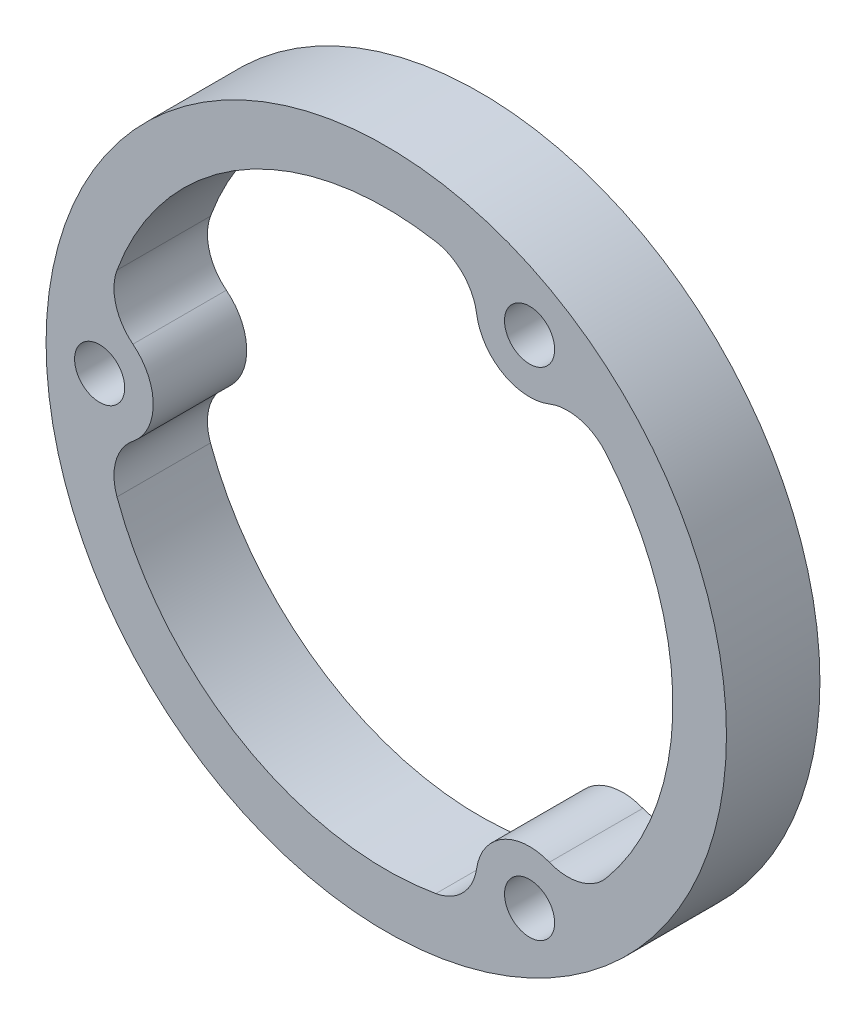
SolidWorks part; units mm, degrees
material "6061-T6 (SS)"
ref_plane "Front Plane" through (0, 0, 0) normal (0, 0, 1) x (1, 0, 0)
ref_plane "Top Plane" through (0, 0, 0) normal (0, 1, 0) x (1, 0, 0)
ref_plane "Right Plane" through (0, 0, 0) normal (1, 0, 0) x (0, 0, -1)
sketch "Sketch1" plane through (0, 0, 0) normal (0, 0, 1) x (1, 0, 0)
  arc A0 (19.0584, -22.136) -> (19.0584, 22.136) centre (0, 0) ccw
  circle A1 centre (0, 0) radius 34.671
  arc A4 (-28.6995, -5.4371) -> (-28.6995, 5.4371) centre (-29.21, 0) ccw
  arc A5 (9.6411, 27.5731) -> (19.0584, 22.136) centre (14.605, 25.2966) ccw
  arc A6 (19.0584, -22.136) -> (9.6411, -27.5731) centre (14.605, -25.2966) ccw
  arc A7 (9.6411, 27.5731) -> (-28.6995, 5.4371) centre (0, 0) ccw
  arc A8 (-28.6995, -5.4371) -> (9.6411, -27.5731) centre (0, 0) ccw
  point P14 (0, 0)
  dimension "D1" = 58.42
  dimension "D2" = 69.342
  dimension "D4" = 3
  dimension "D3" = 30
  dimension "D5" = 120
  dimension "D6" = 120
extrude "Boss-Extrude1" add sketch "Sketch1" along normal blind 9.525
fillet "Fillet1" radius 5.08 6 edges at (9.6411, 27.5731, 4.7625) (19.0584, 22.136, 4.7625) (9.6411, -27.5731, 4.7625) (19.0584, -22.136, 4.7625) (-28.6995, 5.4371, 4.7625) (-28.6995, -5.4371, 4.7625)
sketch "Sketch2" plane through (0, 0, 0) normal (0, 0, -1) x (-1, 0, 0)
  circle A0 centre (-14.605, 25.2966) radius 4.0005
  arc A1 (-16.6198, 20.2209) -> (-9.2019, 24.5036) centre (-14.605, 25.2966) ccw construction
  circle A2 centre (29.21, 0) radius 4.0005
  circle A3 centre (-14.605, -25.2966) radius 4.0005
  point P11 (0, 0)
  dimension "D1" = 8.001
  dimension "D2" = 3
extrude "Cut-Extrude1" cut sketch "Sketch2" against normal blind 5.08
hole_wizard "#10 Clearance Hole1" positions "Sketch3" profile "Sketch4" hole size "#10" standard "ANSI Inch" end condition up to next
sketch "Sketch3" plane through (0, 0, 5.08) normal (0, 0, -1) x (-1, 0, 0)
  circle A0 centre (-14.605, 25.2966) radius 4.0005 construction
  point P0 (-14.605, 25.2966)
  point P13 (29.21, 0)
  point P14 (-14.605, -25.2966)
  point P15 (0, 0)
  dimension "D1" = 3
sketch "Sketch4" plane through (14.605, 25.2966, 5.08) normal (1, 0, 0) x (0, 1, 0)
  line L0 (0, 0) -> (0, 4.445)
  line L1 (0, 4.445) -> (2.5527, 4.445)
  line L2 (2.5527, 4.445) -> (2.5527, 0)
  line L5 (2.5527, 0) -> (0, 0)
  line L11 (0, -6.35) -> (0, 107.95) construction
  dimension "Thru Hole Dia." = 5.1054
  dimension "Thru Hole Depth" = 4.445
